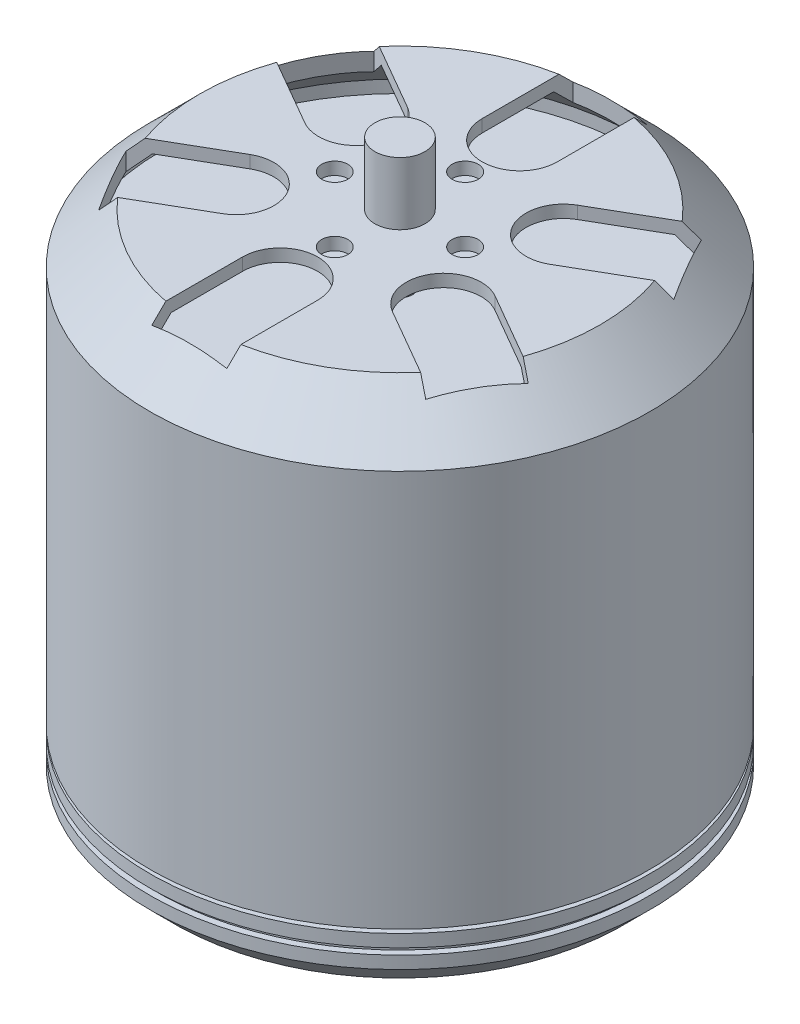
SolidWorks part; units mm, degrees
ref_plane "Front Plane" through (0, 0, 0) normal (0, 0, 1) x (1, 0, 0)
ref_plane "Top Plane" through (0, 0, 0) normal (0, 1, 0) x (1, 0, 0)
ref_plane "Right Plane" through (0, 0, 0) normal (1, 0, 0) x (0, 0, -1)
sketch "Sketch1" plane through (0, 0, 0) normal (0, 0, 1) x (1, 0, 0)
  line L0 (0, 23.3128) -> (0, 0)
  line L1 (10.0544, -22.1872) -> (18, -22.1872)
  line L2 (18, -22.1872) -> (20, -20.1872)
  line L3 (20, -20.1872) -> (20, -19.1872)
  line L4 (20, 14.3128) -> (16, 18.3128)
  line L5 (16, 18.3128) -> (2, 18.3128)
  line L6 (2, 18.3128) -> (2, 23.3128)
  line L7 (2, 23.3128) -> (0, 23.3128)
  line L11 (2, 17.3128) -> (15.5858, 17.3128)
  line L12 (15.5858, 17.3128) -> (19, 13.8986)
  line L13 (19, 13.8986) -> (19, 12.8986)
  line L14 (19, 12.8986) -> (1, 12.8986)
  line L15 (1, 12.8986) -> (1, 16.3128)
  line L16 (1, 16.3128) -> (2, 16.3128)
  line L17 (2, 16.3128) -> (2, 17.3128)
  line L18 (20, -19.1872) -> (19.5, -19.1872)
  line L19 (19.5, -19.1872) -> (19.5, -18.6872)
  line L20 (19.5, -18.6872) -> (20, -18.6872)
  line L21 (20, -17.6872) -> (18, -17.6872)
  line L22 (18, -17.6872) -> (18, -17.3872)
  line L23 (18, -17.3872) -> (20, -17.3872)
  line L24 (20, -18.6872) -> (20, -17.6872)
  line L25 (20, -17.3872) -> (20, 14.3128)
  line L26 (10.0544, -22.1872) -> (0, -22.1872)
  line L27 (0, -22.1872) -> (0, 0)
  point P3 (1, 23.3128)
  point P24 (19.75, -18.6872)
  dimension "D3" = 20
  dimension "D4" = 2
  dimension "D5" = 45.5
  dimension "D6" = 2
  dimension "D7" = 5
  dimension "D8" = 45
  dimension "D10" = 1
  dimension "D11" = 1
  dimension "D12" = 1
  dimension "D13" = 1
  dimension "D14" = 1
  dimension "D15" = 1
  dimension "D16" = 4
  dimension "D17" = 0.5
  dimension "D18" = 0.5
  dimension "D19" = 2
  dimension "D20" = 0.3
  dimension "D21" = 1
  dimension "D22" = 1
  dimension "D23" = 1
revolve "Revolve1" add sketch "Sketch1" angle 360 about L0
sketch "Sketch2" plane through (0, 18.3128, 0) normal (0, 1, 0) x (1, 0, 0)
  line L0 (0, 5.2118) -> (0, 9.5774) construction
  line L1 (-3, 9.5774) -> (-3, 16.8382)
  line L2 (-3, 16.8382) -> (3, 16.8382)
  line L3 (3, 16.8382) -> (3, 9.5774)
  line L4 (16.0823, 5.821) -> (9.7943, 2.1906)
  line L5 (13.0823, 11.0172) -> (16.0823, 5.821)
  line L6 (6.7943, 7.3868) -> (13.0823, 11.0172)
  line L7 (13.0823, -11.0172) -> (6.7943, -7.3868)
  line L8 (16.0823, -5.821) -> (13.0823, -11.0172)
  line L9 (9.7943, -2.1906) -> (16.0823, -5.821)
  line L10 (-3, -16.8382) -> (-3, -9.5774)
  line L11 (3, -16.8382) -> (-3, -16.8382)
  line L12 (3, -9.5774) -> (3, -16.8382)
  line L13 (-16.0823, -5.821) -> (-9.7943, -2.1906)
  line L14 (-13.0823, -11.0172) -> (-16.0823, -5.821)
  line L15 (-6.7943, -7.3868) -> (-13.0823, -11.0172)
  line L16 (-13.0823, 11.0172) -> (-6.7943, 7.3868)
  line L17 (-16.0823, 5.821) -> (-13.0823, 11.0172)
  line L18 (-9.7943, 2.1906) -> (-16.0823, 5.821)
  circle A0 centre (0, 0) radius 5.2118 construction
  circle A1 centre (0, 0) radius 9.9437 construction
  circle A2 centre (0, -5.2118) radius 1.0462
  circle A3 centre (-5.2118, 0) radius 1.0462
  circle A4 centre (0, 5.2118) radius 1.0462
  circle A5 centre (5.2118, 0) radius 1.0462
  arc A6 (-3, 9.5774) -> (3, 9.5774) centre (0, 9.5774) ccw
  arc A7 (6.7943, 7.3868) -> (9.7943, 2.1906) centre (8.2943, 4.7887) ccw
  arc A8 (9.7943, -2.1906) -> (6.7943, -7.3868) centre (8.2943, -4.7887) ccw
  arc A9 (3, -9.5774) -> (-3, -9.5774) centre (0, -9.5774) ccw
  arc A10 (-6.7943, -7.3868) -> (-9.7943, -2.1906) centre (-8.2943, -4.7887) ccw
  arc A11 (-9.7943, 2.1906) -> (-6.7943, 7.3868) centre (-8.2943, 4.7887) ccw
  point P15 (0, 0)
  point P45 (0, 0)
  dimension "D2" = 6
  dimension "D1" = 4
  dimension "D3" = 6
extrude "Cut-Extrude1" cut sketch "Sketch2" against normal blind 4
sketch "Sketch3" plane through (0, -22.1872, 0) normal (0, -1, 0) x (1, 0, 0)
  circle A0 centre (0, 0) radius 9.5 construction
  circle A1 centre (0, 0) radius 12.5 construction
  circle A2 centre (0, -9.5) radius 1
  circle A3 centre (-12.5, 0) radius 1
  circle A4 centre (0, 9.5) radius 1
  circle A5 centre (12.5, 0) radius 1
  dimension "D1" = 19
  dimension "D2" = 25
  dimension "D3" = 2
extrude "Cut-Extrude2" cut sketch "Sketch3" against normal blind 3
